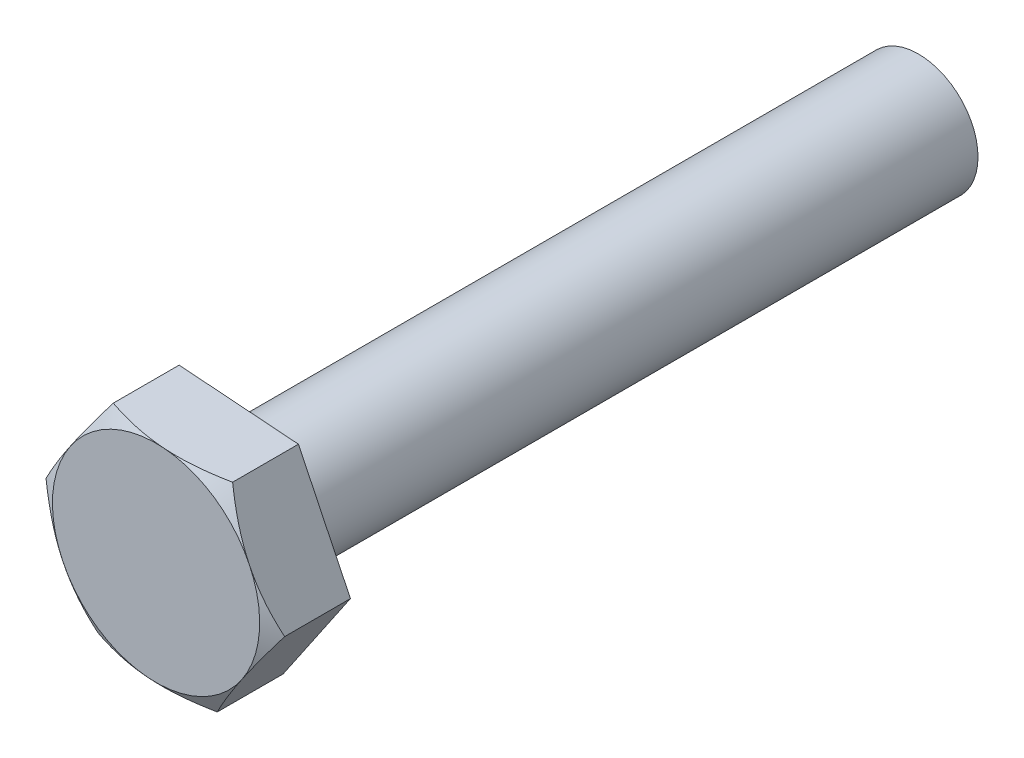
SolidWorks part; units mm, degrees
ref_plane "Front Plane" through (0, 0, 0) normal (0, 0, 1) x (1, 0, 0)
ref_plane "Top Plane" through (0, 0, 0) normal (0, 1, 0) x (1, 0, 0)
ref_plane "Right Plane" through (0, 0, 0) normal (1, 0, 0) x (0, 0, -1)
sketch "Sketch1" plane through (0, 0, 0) normal (0, 0, 1) x (1, 0, 0)
  line L1 (5.091, 7.4822) -> (-3.9343, 8.1501)
  line L2 (-3.9343, 8.1501) -> (-9.0253, 0.6678)
  line L3 (-9.0253, 0.6678) -> (-5.091, -7.4822)
  line L4 (-5.091, -7.4822) -> (3.9343, -8.1501)
  line L5 (3.9343, -8.1501) -> (9.0253, -0.6678)
  line L6 (9.0253, -0.6678) -> (5.091, 7.4822)
  circle A0 centre (0, 0) radius 9.05 construction
  dimension "D1" = 18.1
extrude "Boss-Extrude1" add sketch "Sketch1" along normal blind 5.68
sketch "Sketch2" plane through (0, 0, 5.68) normal (0, 0, 1) x (1, 0, 0)
  line L0 (-3.9343, 8.1501) -> (-9.0253, 0.6678) construction
  circle A0 centre (0, 0) radius 7.8375
extrude "Cut-Extrude1" cut sketch "Sketch2" against normal blind 5.68 draft 60 flip side to cut
sketch "Sketch3" plane through (0, 0, 0) normal (0, 0, -1) x (-1, 0, 0)
  circle A0 centre (0, 0) radius 4.5
  dimension "D1" = 9
extrude "Boss-Extrude2" add sketch "Sketch3" along normal blind 52
